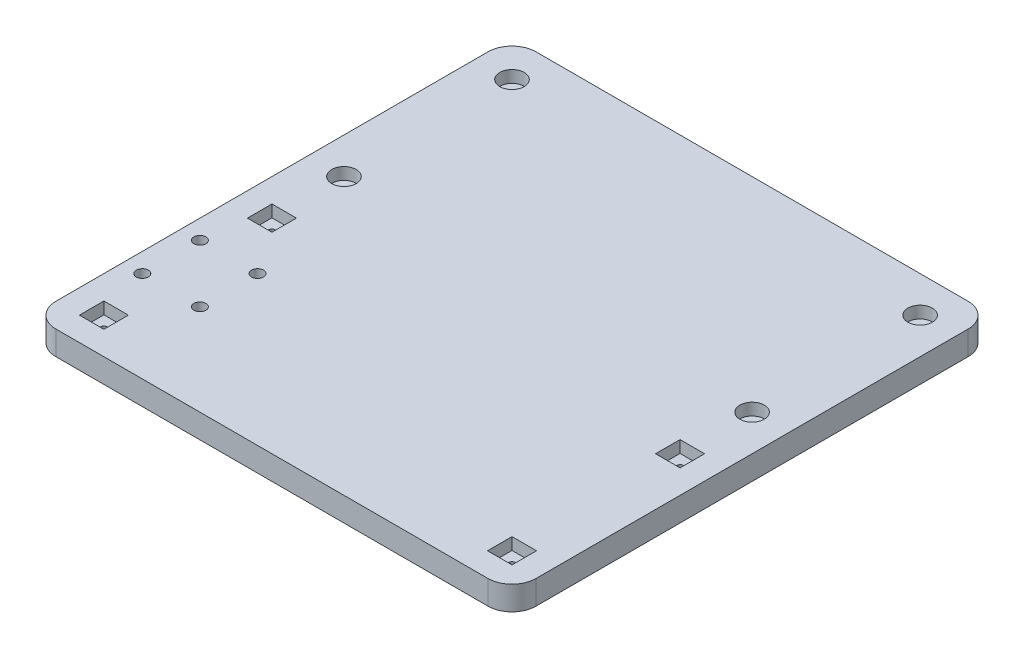
SolidWorks part; units mm, degrees
ref_plane "正面" through (0, 0, 0) normal (0, 0, 1) x (1, 0, 0)
ref_plane "平面" through (0, 0, 0) normal (0, 1, 0) x (1, 0, 0)
ref_plane "右側面" through (0, 0, 0) normal (1, 0, 0) x (0, 0, -1)
sketch "ｽｹｯﾁ1" plane through (0, 0, 0) normal (0, 1, 0) x (1, 0, 0)
  line L1 (-100, -100) -> (100, -100)
  line L2 (-100, -100) -> (-100, 100)
  line L3 (-100, 100) -> (100, 100)
  line L4 (100, -100) -> (100, 100)
  line L5 (-100, -100) -> (100, 100) construction
  line L6 (-100, 100) -> (100, -100) construction
  point P0 (0, 0)
  dimension "D1" = 200
  dimension "D2" = 200
extrude "ﾎﾞｽ - 押し出し1" add sketch "ｽｹｯﾁ1" along normal blind 10
sketch "ｽｹｯﾁ2" plane through (0, 10, 0) normal (0, 1, 0) x (1, 0, 0)
  line L1 (-90.1, -20.1) -> (-79.9, -20.1)
  line L2 (-90.1, -20.1) -> (-90.1, -9.9)
  line L3 (-90.1, -9.9) -> (-79.9, -9.9)
  line L4 (-79.9, -20.1) -> (-79.9, -9.9)
  line L5 (-90.1, -20.1) -> (-79.9, -9.9) construction
  line L6 (-90.1, -9.9) -> (-79.9, -20.1) construction
  line L7 (79.9, -20.1) -> (90.1, -20.1)
  line L8 (79.9, -20.1) -> (79.9, -9.9)
  line L9 (79.9, -9.9) -> (90.1, -9.9)
  line L10 (90.1, -20.1) -> (90.1, -9.9)
  line L11 (79.9, -20.1) -> (90.1, -9.9) construction
  line L12 (79.9, -9.9) -> (90.1, -20.1) construction
  line L13 (-90.1, -90.1) -> (-79.9, -90.1)
  line L14 (-90.1, -90.1) -> (-90.1, -79.9)
  line L15 (-90.1, -79.9) -> (-79.9, -79.9)
  line L16 (-79.9, -90.1) -> (-79.9, -79.9)
  line L17 (-90.1, -90.1) -> (-79.9, -79.9) construction
  line L18 (-90.1, -79.9) -> (-79.9, -90.1) construction
  line L19 (79.9, -90.1) -> (90.1, -90.1)
  line L20 (79.9, -90.1) -> (79.9, -79.9)
  line L21 (79.9, -79.9) -> (90.1, -79.9)
  line L22 (90.1, -90.1) -> (90.1, -79.9)
  line L23 (79.9, -90.1) -> (90.1, -79.9) construction
  line L24 (79.9, -79.9) -> (90.1, -90.1) construction
  line L25 (-100, 100) -> (-100, -100) construction
  line L26 (100, -100) -> (100, 100) construction
  line L27 (-100, -100) -> (100, -100) construction
  point P0 (-85, -15)
  point P5 (85, -15)
  point P10 (-85, -85)
  point P15 (85, -85)
  point P20 (0, 0)
  point P21 (0, 0)
  point P22 (0, 0)
  point P24 (0, 0)
  dimension "D1" = 10.2
  dimension "D2" = 15
  dimension "D3" = 15
  dimension "D4" = 15
  dimension "D5" = 15
extrude "ｶｯﾄ - 押し出し3" cut sketch "ｽｹｯﾁ2" against normal blind 5
fillet "ﾌｨﾚｯﾄ1" radius 10 4 edges at (100, 5, -100) (100, 5, 100) (-100, 5, 100) (-100, 5, -100)
sketch "ｽｹｯﾁ3" plane through (0, 10, 0) normal (0, 1, 0) x (1, 0, 0)
  line L0 (90, 100) -> (-90, 100) construction
  line L1 (-100, 90) -> (-100, -90) construction
  line L2 (100, -90) -> (100, 90) construction
  circle A0 centre (-85, 85) radius 5.1
  circle A1 centre (85, 85) radius 5.1
  circle A2 centre (-85, 15) radius 5.1
  circle A3 centre (85, 15) radius 5.1
  dimension "D1" = 10.2
  dimension "D2" = 15
  dimension "D3" = 15
  dimension "D4" = 15
  dimension "D5" = 15
extrude "ｶｯﾄ - 押し出し1" cut sketch "ｽｹｯﾁ3" against normal blind 5
sketch "ｽｹｯﾁ4" plane through (0, 10, 0) normal (0, 1, 0) x (1, 0, 0)
  line L0 (-90.1, -90.1) -> (-79.9, -90.1) construction
  line L1 (-85, -9.9) -> (-85, -90.1) construction
  line L2 (-85, -50) -> (-80, -50) construction
  line L3 (-100, 90) -> (-100, -90) construction
  line L4 (-79.9, -9.9) -> (-90.1, -9.9) construction
  circle A4 centre (-68, -38) radius 2.5
  circle A5 centre (-68, -62) radius 2.5
  circle A6 centre (-92, -62) radius 2.5
  circle A7 centre (-92, -38) radius 2.5
  point P2 (0, 0)
  point P3 (-80, -50)
  point P8 (-85, -90.1)
  point P9 (0, 0)
  dimension "D2" = 24
  dimension "D3" = 24
  dimension "D6" = 5
  dimension "D1" = 20
  dimension "D4" = 12
  dimension "D5" = 12
extrude "ｶｯﾄ - 押し出し2" cut sketch "ｽｹｯﾁ4" against normal through all
sketch "ｽｹｯﾁ5" plane through (0, 0, 0) normal (0, -1, 0) x (1, 0, 0)
  line L0 (-90, 100) -> (90, 100) construction
  line L1 (-100, -90) -> (-100, 90) construction
  line L2 (100, 90) -> (100, -90) construction
  circle A0 centre (-85, 85) radius 1.5
  circle A1 centre (85, 85) radius 1.5
  circle A2 centre (-85, 15) radius 1.5
  circle A3 centre (85, 15) radius 1.5
  point P8 (0, 0)
  point P9 (0, 0)
  point P10 (0, 0)
  point P11 (0, 0)
  point P12 (0, 0)
  dimension "D5" = 3
  dimension "D1" = 15
  dimension "D2" = 15
  dimension "D3" = 15
  dimension "D4" = 15
extrude "ｶｯﾄ - 押し出し4" cut sketch "ｽｹｯﾁ5" against normal through all
